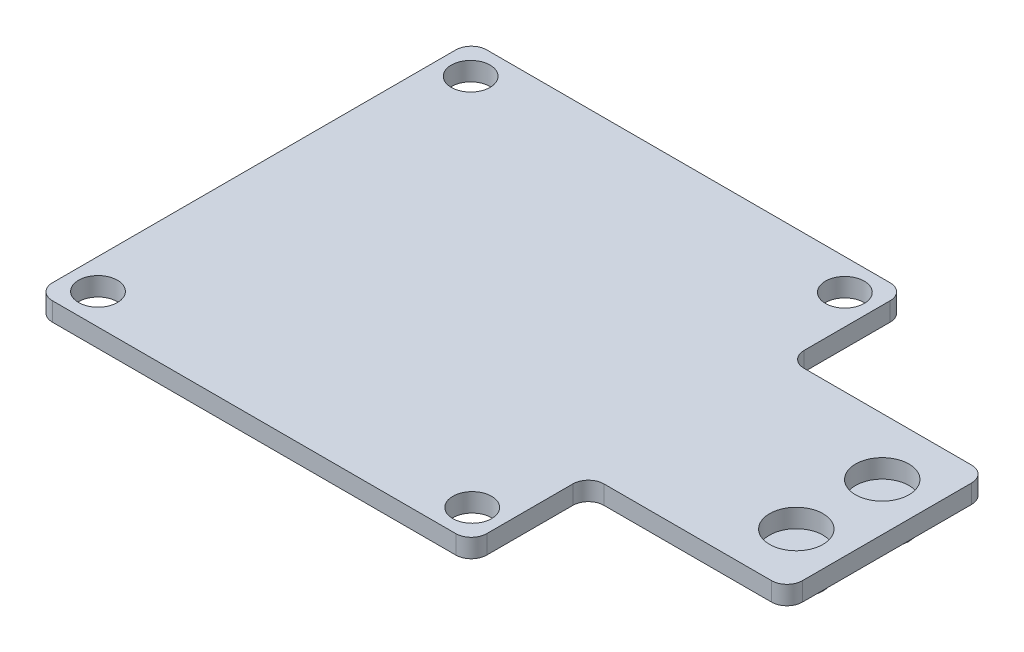
SolidWorks part; units mm, degrees
ref_plane "Front Plane" through (0, 0, 0) normal (0, 0, 1) x (1, 0, 0)
ref_plane "Top Plane" through (0, 0, 0) normal (0, 1, 0) x (1, 0, 0)
ref_plane "Right Plane" through (0, 0, 0) normal (1, 0, 0) x (0, 0, -1)
sketch "Sketch1" plane through (0, 0, 0) normal (0, 1, 0) x (1, 0, 0)
  line L0 (-50.7462, 35.4274) -> (-17.7262, 35.4274)
  line L1 (-52.0162, 34.1574) -> (-52.0162, 1.1374)
  line L2 (-50.7462, -0.1326) -> (-17.7262, -0.1326)
  line L3 (-16.4562, 1.1374) -> (-16.4562, 8.1859)
  line L5 (-15.1862, 25.8389) -> (-1.4702, 25.8389)
  line L6 (-0.2002, 24.5689) -> (-0.2002, 10.7259)
  line L9 (-15.1862, 9.4559) -> (-1.4702, 9.4559)
  line L11 (-16.4562, 27.1089) -> (-16.4562, 34.1574)
  circle A0 centre (-49.5397, 32.9001) radius 1.5875
  circle A1 centre (-18.9073, 32.9001) radius 1.5875
  circle A2 centre (-18.9073, 2.3947) radius 1.5875
  circle A3 centre (-49.5397, 2.3947) radius 1.5875
  arc A4 (-50.7462, 35.4274) -> (-52.0162, 34.1574) centre (-50.7462, 34.1574) ccw
  arc A5 (-52.0162, 1.1374) -> (-50.7462, -0.1326) centre (-50.7462, 1.1374) ccw
  arc A6 (-17.7262, -0.1326) -> (-16.4562, 1.1374) centre (-17.7262, 1.1374) ccw
  arc A7 (-17.7262, 35.4274) -> (-16.4562, 34.1574) centre (-17.7262, 34.1574) cw
  circle A8 centre (-4.1118, 21.1653) radius 2.1844
  circle A10 centre (-4.1118, 14.1295) radius 2.1844
  arc A12 (-1.4702, 25.8389) -> (-0.2002, 24.5689) centre (-1.4702, 24.5689) cw
  arc A13 (-1.4702, 9.4559) -> (-0.2002, 10.7259) centre (-1.4702, 10.7259) ccw
  arc A14 (-15.1862, 9.4559) -> (-16.4562, 8.1859) centre (-15.1862, 8.1859) ccw
  arc A15 (-16.4562, 27.1089) -> (-15.1862, 25.8389) centre (-15.1862, 27.1089) ccw
  point P38 (-16.4562, 25.8389)
  dimension "D1" = 1.27
  dimension "D2" = 1.27
extrude "Boss-Extrude2" add sketch "Sketch1" along normal blind 1.524
sketch "Sketch3" plane through (0, 0, 0) normal (0, -1, 0) x (1, 0, 0)
  circle A0 centre (-4.1118, -14.1295) radius 2.1844
  circle A1 centre (-4.1118, -21.1653) radius 2.1844
extrude "Boss-Extrude4" add sketch "Sketch3" along normal blind 1.778 separate body
sketch "Sketch6" plane through (0, 0, 0) normal (0, -1, 0) x (1, 0, 0)
  circle A0 centre (-4.1118, -14.1295) radius 2.1844
  circle A1 centre (-4.1118, -21.1653) radius 2.1844
